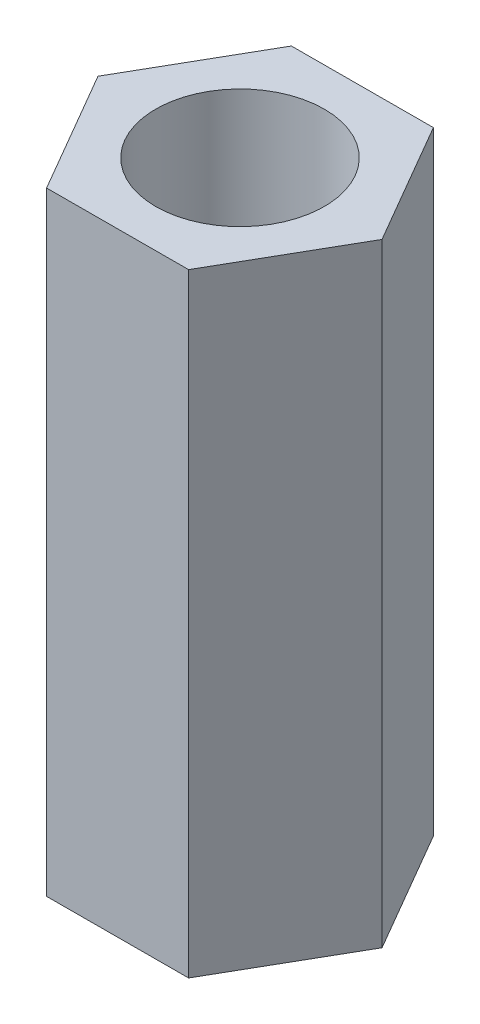
SolidWorks part; units mm, degrees
ref_plane "前视基准面" through (0, 0, 0) normal (0, 0, 1) x (1, 0, 0)
ref_plane "上视基准面" through (0, 0, 0) normal (0, 1, 0) x (1, 0, 0)
ref_plane "右视基准面" through (0, 0, 0) normal (1, 0, 0) x (0, 0, -1)
sketch "草图1" plane through (0, 0, 0) normal (0, 1, 0) x (1, 0, 0)
  line L1 (1.1596, -1.9971) -> (2.3094, 0.0057)
  line L2 (2.3094, 0.0057) -> (1.1498, 2.0028)
  line L3 (1.1498, 2.0028) -> (-1.1596, 1.9971)
  line L4 (-1.1596, 1.9971) -> (-2.3094, -0.0057)
  line L5 (-2.3094, -0.0057) -> (-1.1498, -2.0028)
  line L6 (-1.1498, -2.0028) -> (1.1596, -1.9971)
  circle A0 centre (0, 0) radius 2 construction
  point P1 (1.7296, 1.0043)
  dimension "D1" = 2
extrude "凸台-拉伸1" add sketch "草图1" along normal blind 10
sketch "草图2" plane through (0, 0, 0) normal (0, 1, 0) x (1, 0, 0)
  circle A0 centre (0, 0) radius 1.375
  dimension "D1" = 2.75
extrude "切除-拉伸1" cut sketch "草图2" along normal blind 10
